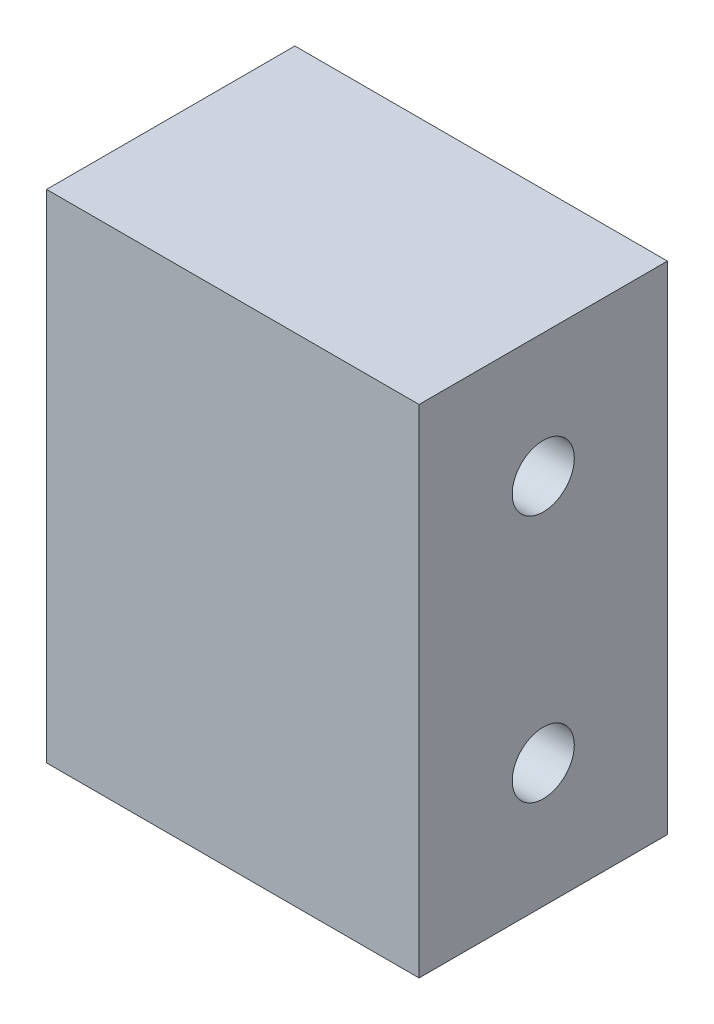
SolidWorks part; units mm, degrees
ref_plane "Спереди" through (0, 0, 0) normal (0, 0, 1) x (1, 0, 0)
ref_plane "Сверху" through (0, 0, 0) normal (0, 1, 0) x (1, 0, 0)
ref_plane "Справа" through (0, 0, 0) normal (1, 0, 0) x (0, 0, -1)
sketch "Эскиз1" plane through (0, 0, 0) normal (1, 0, 0) x (0, 0, -1)
  line L1 (0, 0) -> (40, 0)
  line L2 (0, 0) -> (0, 80)
  line L3 (0, 80) -> (40, 80)
  line L4 (40, 0) -> (40, 80)
  circle A0 centre (20, 60) radius 5
  circle A1 centre (20, 20) radius 5
  dimension "D1" = 10
  dimension "D2" = 10
  dimension "D3" = 40
  dimension "D4" = 20
  dimension "D5" = 20
  dimension "D6" = 40
  dimension "D7" = 20
  dimension "D8" = 80
extrude "Бобышка-Вытянуть1" add sketch "Эскиз1" along normal blind 60
